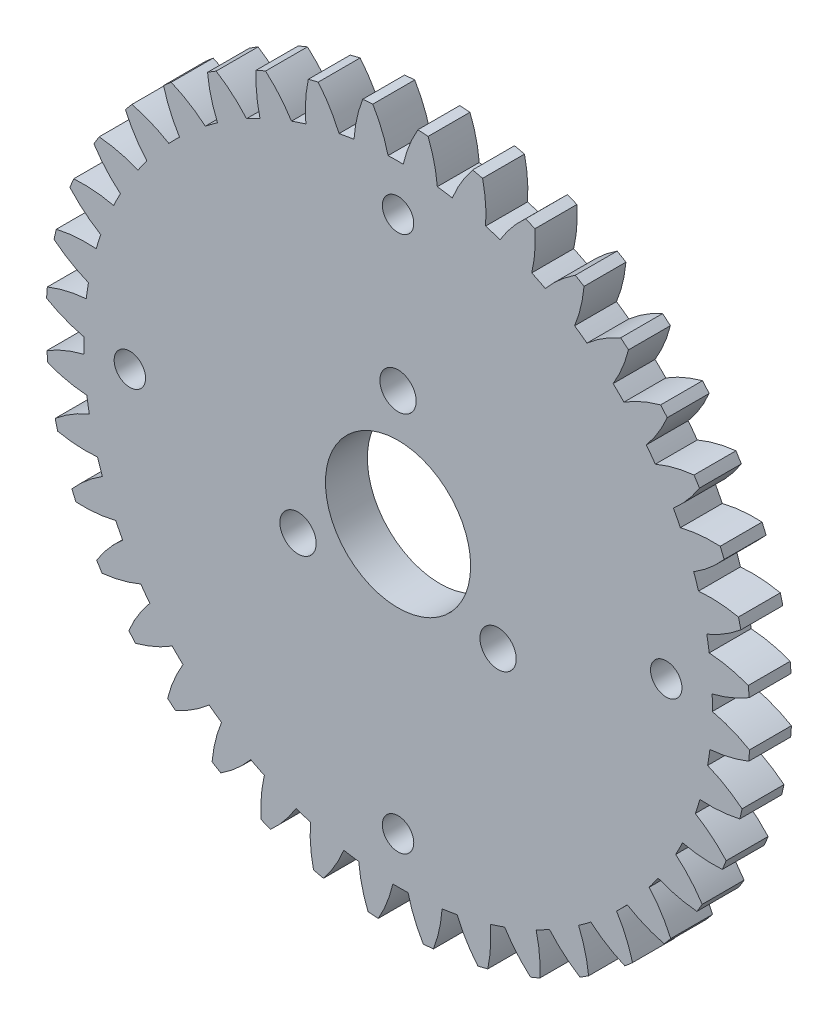
SolidWorks part; units mm, degrees
ref_plane "Front Plane" through (0, 0, 0) normal (0, 0, 1) x (1, 0, 0)
ref_plane "Top Plane" through (0, 0, 0) normal (0, 1, 0) x (1, 0, 0)
ref_plane "Right Plane" through (0, 0, 0) normal (1, 0, 0) x (0, 0, -1)
sketch "Sketch1" plane through (0, 0, 0) normal (0, 0, 1) x (1, 0, 0)
  line L0 (-15.1554, -8.75) -> (0, 0) construction
  line L1 (0, 0) -> (0, 17.5) construction
  line L2 (0, 0) -> (15.1554, -8.75) construction
  line L3 (0, 40.64) -> (0, 0) construction
  line L4 (-40.64, 0) -> (0, 0) construction
  circle A0 centre (0, 0) radius 11
  circle A1 centre (0, 0) radius 17.5 construction
  circle A2 centre (0, 17.5) radius 2.75
  circle A3 centre (15.1554, -8.75) radius 2.75
  circle A4 centre (-15.1554, -8.75) radius 2.75
  circle A5 centre (0, 40.64) radius 2.3812
  circle A7 centre (40.64, 0) radius 2.3813
  circle A8 centre (0, -40.64) radius 2.3813
  circle A9 centre (-40.64, 0) radius 2.3813
  point P12 (0, 0)
  point P22 (0, 0)
  arc B0 (-53.2553, 3.0046) -> (-47.6173, 0.7826) centre (-43.069, 20.587) ccw
  arc B1 (-47.6173, 0.7826) -> (-47.5997, -1.5139) centre (0, 0) ccw
  arc B2 (-47.5997, -1.5139) -> (-53.2029, -3.8222) centre (-42.7477, -21.2461) ccw
  arc B3 (-53.2029, -3.8222) -> (-53.0697, -5.3634) centre (0, 0) ccw
  arc B4 (-53.0697, -5.3634) -> (-47.1535, -6.676) centre (-45.7593, 13.5961) ccw
  arc B5 (-47.1535, -6.676) -> (-46.7768, -8.9415) centre (0, 0) ccw
  arc B6 (-46.7768, -8.9415) -> (-51.9499, -12.0979) centre (-38.8978, -27.6718) ccw
  arc B7 (-51.9499, -12.0979) -> (-51.5773, -13.5993) centre (0, 0) ccw
  arc B8 (-51.5773, -13.5993) -> (-45.5286, -13.9703) centre (-47.3228, 6.2704) ccw
  arc B9 (-45.5286, -13.9703) -> (-44.8022, -16.1489) centre (0, 0) ccw
  arc B10 (-44.8022, -16.1489) -> (-49.4178, -20.0758) centre (-34.0901, -33.416) ccw
  arc B11 (-49.4178, -20.0758) -> (-48.8149, -21.5003) centre (0, 0) ccw
  arc B12 (-48.8149, -21.5003) -> (-42.7826, -20.9205) centre (-47.7211, -1.2098) ccw
  arc B13 (-42.7826, -20.9205) -> (-41.7243, -22.9587) centre (0, 0) ccw
  arc B14 (-41.7243, -22.9587) -> (-45.6688, -27.5592) centre (-28.4429, -38.3375) ccw
  arc B15 (-45.6688, -27.5592) -> (-44.8505, -28.8719) centre (0, 0) ccw
  arc B16 (-44.8505, -28.8719) -> (-38.9832, -27.3556) centre (-46.9443, -8.6601) ccw
  arc B17 (-38.9832, -27.3556) -> (-37.6191, -29.2031) centre (0, 0) ccw
  arc B18 (-37.6191, -29.2031) -> (-40.7954, -34.3641) centre (-22.0955, -42.3149) ccw
  arc B19 (-40.7954, -34.3641) -> (-39.7818, -35.5326) centre (0, 0) ccw
  arc B20 (-39.7818, -35.5326) -> (-34.2239, -33.1172) centre (-45.0116, -15.8972) ccw
  arc B21 (-34.2239, -33.1172) -> (-32.5876, -34.7285) centre (0, 0) ccw
  arc B22 (-32.5876, -34.7285) -> (-34.9174, -40.3228) centre (-15.2039, -45.2505) ccw
  arc B23 (-34.9174, -40.3228) -> (-33.7334, -41.3184) centre (0, 0) ccw
  arc B24 (-33.7334, -41.3184) -> (-28.6219, -38.0632) centre (-41.9706, -22.7428) ccw
  arc B25 (-28.6219, -38.0632) -> (-26.7536, -39.3988) centre (0, 0) ccw
  arc B26 (-26.7536, -39.3988) -> (-28.1796, -45.2887) centre (-7.938, -47.0718) ccw
  arc B27 (-28.1796, -45.2887) -> (-26.8545, -46.0868) centre (0, 0) ccw
  arc B28 (-26.8545, -46.0868) -> (-22.3151, -42.072) centre (-37.8961, -29.0284) ccw
  arc B29 (-22.3151, -42.072) -> (-20.2609, -43.0989) centre (0, 0) ccw
  arc B30 (-20.2609, -43.0989) -> (-20.748, -49.1394) centre (-0.4766, -47.734) ccw
  arc B31 (-20.748, -49.1394) -> (-19.3143, -49.7203) centre (0, 0) ccw
  arc B32 (-19.3143, -49.7203) -> (-15.4588, -45.0449) centre (-32.8885, -34.5993) ccw
  arc B33 (-15.4588, -45.0449) -> (-13.2693, -45.7378) centre (0, 0) ccw
  arc B34 (-13.2693, -45.7378) -> (-12.8054, -51.7801) centre (6.9965, -47.2209) ccw
  arc B35 (-12.8054, -51.7801) -> (-11.2986, -52.1296) centre (0, 0) ccw
  arc B36 (-11.2986, -52.1296) -> (-8.2219, -46.9086) centre (-27.071, -39.3182) ccw
  arc B37 (-8.2219, -46.9086) -> (-5.951, -47.2505) centre (0, 0) ccw
  arc B38 (-5.951, -47.2505) -> (-4.5476, -53.1458) centre (14.2973, -45.545) ccw
  arc B39 (-4.5476, -53.1458) -> (-3.0046, -53.2553) centre (0, 0) ccw
  arc B40 (-3.0046, -53.2553) -> (-0.7826, -47.6173) centre (-20.587, -43.069) ccw
  arc B41 (-0.7826, -47.6173) -> (1.5139, -47.5997) centre (0, 0) ccw
  arc B42 (1.5139, -47.5997) -> (3.8222, -53.2029) centre (21.2461, -42.7477) ccw
  arc B43 (3.8222, -53.2029) -> (5.3634, -53.0697) centre (0, 0) ccw
  arc B44 (5.3634, -53.0697) -> (6.676, -47.1535) centre (-13.5961, -45.7593) ccw
  arc B45 (6.676, -47.1535) -> (8.9415, -46.7768) centre (0, 0) ccw
  arc B46 (8.9415, -46.7768) -> (12.0979, -51.9499) centre (27.6718, -38.8978) ccw
  arc B47 (12.0979, -51.9499) -> (13.5993, -51.5773) centre (0, 0) ccw
  arc B48 (13.5993, -51.5773) -> (13.9703, -45.5286) centre (-6.2704, -47.3228) ccw
  arc B49 (13.9703, -45.5286) -> (16.1489, -44.8022) centre (0, 0) ccw
  arc B50 (16.1489, -44.8022) -> (20.0758, -49.4178) centre (33.416, -34.0901) ccw
  arc B51 (20.0758, -49.4178) -> (21.5003, -48.8149) centre (0, 0) ccw
  arc B52 (21.5003, -48.8149) -> (20.9205, -42.7826) centre (1.2098, -47.7211) ccw
  arc B53 (20.9205, -42.7826) -> (22.9587, -41.7243) centre (0, 0) ccw
  arc B54 (22.9587, -41.7243) -> (27.5592, -45.6688) centre (38.3375, -28.4429) ccw
  arc B55 (27.5592, -45.6688) -> (28.8719, -44.8505) centre (0, 0) ccw
  arc B56 (28.8719, -44.8505) -> (27.3556, -38.9832) centre (8.6601, -46.9443) ccw
  arc B57 (27.3556, -38.9832) -> (29.2031, -37.6191) centre (0, 0) ccw
  arc B58 (29.2031, -37.6191) -> (34.3641, -40.7954) centre (42.3149, -22.0955) ccw
  arc B59 (34.3641, -40.7954) -> (35.5326, -39.7818) centre (0, 0) ccw
  arc B60 (35.5326, -39.7818) -> (33.1172, -34.2239) centre (15.8972, -45.0116) ccw
  arc B61 (33.1172, -34.2239) -> (34.7285, -32.5876) centre (0, 0) ccw
  arc B62 (34.7285, -32.5876) -> (40.3228, -34.9174) centre (45.2505, -15.2039) ccw
  arc B63 (40.3228, -34.9174) -> (41.3184, -33.7334) centre (0, 0) ccw
  arc B64 (41.3184, -33.7334) -> (38.0632, -28.6219) centre (22.7428, -41.9706) ccw
  arc B65 (38.0632, -28.6219) -> (39.3988, -26.7536) centre (0, 0) ccw
  arc B66 (39.3988, -26.7536) -> (45.2887, -28.1796) centre (47.0718, -7.938) ccw
  arc B67 (45.2887, -28.1796) -> (46.0868, -26.8545) centre (0, 0) ccw
  arc B68 (46.0868, -26.8545) -> (42.072, -22.3151) centre (29.0284, -37.8961) ccw
  arc B69 (42.072, -22.3151) -> (43.0989, -20.2609) centre (0, 0) ccw
  arc B70 (43.0989, -20.2609) -> (49.1394, -20.748) centre (47.734, -0.4766) ccw
  arc B71 (49.1394, -20.748) -> (49.7203, -19.3143) centre (0, 0) ccw
  arc B72 (49.7203, -19.3143) -> (45.0449, -15.4588) centre (34.5993, -32.8885) ccw
  arc B73 (45.0449, -15.4588) -> (45.7378, -13.2693) centre (0, 0) ccw
  arc B74 (45.7378, -13.2693) -> (51.7801, -12.8054) centre (47.2209, 6.9965) ccw
  arc B75 (51.7801, -12.8054) -> (52.1296, -11.2986) centre (0, 0) ccw
  arc B76 (52.1296, -11.2986) -> (46.9086, -8.2219) centre (39.3182, -27.071) ccw
  arc B77 (46.9086, -8.2219) -> (47.2505, -5.951) centre (0, 0) ccw
  arc B78 (47.2505, -5.951) -> (53.1458, -4.5476) centre (45.545, 14.2973) ccw
  arc B79 (53.1458, -4.5476) -> (53.2553, -3.0046) centre (0, 0) ccw
  arc B80 (53.2553, -3.0046) -> (47.6173, -0.7826) centre (43.069, -20.587) ccw
  arc B81 (47.6173, -0.7826) -> (47.5997, 1.5139) centre (0, 0) ccw
  arc B82 (47.5997, 1.5139) -> (53.2029, 3.8222) centre (42.7477, 21.2461) ccw
  arc B83 (53.2029, 3.8222) -> (53.0697, 5.3634) centre (0, 0) ccw
  arc B84 (53.0697, 5.3634) -> (47.1535, 6.676) centre (45.7593, -13.5961) ccw
  arc B85 (47.1535, 6.676) -> (46.7768, 8.9415) centre (0, 0) ccw
  arc B86 (46.7768, 8.9415) -> (51.9499, 12.0979) centre (38.8978, 27.6718) ccw
  arc B87 (51.9499, 12.0979) -> (51.5773, 13.5993) centre (0, 0) ccw
  arc B88 (51.5773, 13.5993) -> (45.5286, 13.9703) centre (47.3228, -6.2704) ccw
  arc B89 (45.5286, 13.9703) -> (44.8022, 16.1489) centre (0, 0) ccw
  arc B90 (44.8022, 16.1489) -> (49.4178, 20.0758) centre (34.0901, 33.416) ccw
  arc B91 (49.4178, 20.0758) -> (48.8149, 21.5003) centre (0, 0) ccw
  arc B92 (48.8149, 21.5003) -> (42.7826, 20.9205) centre (47.7211, 1.2098) ccw
  arc B93 (42.7826, 20.9205) -> (41.7243, 22.9587) centre (0, 0) ccw
  arc B94 (41.7243, 22.9587) -> (45.6688, 27.5592) centre (28.4429, 38.3375) ccw
  arc B95 (45.6688, 27.5592) -> (44.8505, 28.8719) centre (0, 0) ccw
  arc B96 (44.8505, 28.8719) -> (38.9832, 27.3556) centre (46.9443, 8.6601) ccw
  arc B97 (38.9832, 27.3556) -> (37.6191, 29.2031) centre (0, 0) ccw
  arc B98 (37.6191, 29.2031) -> (40.7954, 34.3641) centre (22.0955, 42.3149) ccw
  arc B99 (40.7954, 34.3641) -> (39.7818, 35.5326) centre (0, 0) ccw
  arc B100 (39.7818, 35.5326) -> (34.2239, 33.1172) centre (45.0116, 15.8972) ccw
  arc B101 (34.2239, 33.1172) -> (32.5876, 34.7285) centre (0, 0) ccw
  arc B102 (32.5876, 34.7285) -> (34.9174, 40.3228) centre (15.2039, 45.2505) ccw
  arc B103 (34.9174, 40.3228) -> (33.7334, 41.3184) centre (0, 0) ccw
  arc B104 (33.7334, 41.3184) -> (28.6219, 38.0632) centre (41.9706, 22.7428) ccw
  arc B105 (28.6219, 38.0632) -> (26.7536, 39.3988) centre (0, 0) ccw
  arc B106 (26.7536, 39.3988) -> (28.1796, 45.2887) centre (7.938, 47.0718) ccw
  arc B107 (28.1796, 45.2887) -> (26.8545, 46.0868) centre (0, 0) ccw
  arc B108 (26.8545, 46.0868) -> (22.3151, 42.072) centre (37.8961, 29.0284) ccw
  arc B109 (22.3151, 42.072) -> (20.2609, 43.0989) centre (0, 0) ccw
  arc B110 (20.2609, 43.0989) -> (20.748, 49.1394) centre (0.4766, 47.734) ccw
  arc B111 (20.748, 49.1394) -> (19.3143, 49.7203) centre (0, 0) ccw
  arc B112 (19.3143, 49.7203) -> (15.4588, 45.0449) centre (32.8885, 34.5993) ccw
  arc B113 (15.4588, 45.0449) -> (13.2693, 45.7378) centre (0, 0) ccw
  arc B114 (13.2693, 45.7378) -> (12.8054, 51.7801) centre (-6.9965, 47.2209) ccw
  arc B115 (12.8054, 51.7801) -> (11.2986, 52.1296) centre (0, 0) ccw
  arc B116 (11.2986, 52.1296) -> (8.2219, 46.9086) centre (27.071, 39.3182) ccw
  arc B117 (8.2219, 46.9086) -> (5.951, 47.2505) centre (0, 0) ccw
  arc B118 (5.951, 47.2505) -> (4.5476, 53.1458) centre (-14.2973, 45.545) ccw
  arc B119 (4.5476, 53.1458) -> (3.0046, 53.2553) centre (0, 0) ccw
  arc B120 (3.0046, 53.2553) -> (0.7826, 47.6173) centre (20.587, 43.069) ccw
  arc B121 (0.7826, 47.6173) -> (-1.5139, 47.5997) centre (0, 0) ccw
  arc B122 (-1.5139, 47.5997) -> (-3.8222, 53.2029) centre (-21.2461, 42.7477) ccw
  arc B123 (-3.8222, 53.2029) -> (-5.3634, 53.0697) centre (0, 0) ccw
  arc B124 (-5.3634, 53.0697) -> (-6.676, 47.1535) centre (13.5961, 45.7593) ccw
  arc B125 (-6.676, 47.1535) -> (-8.9415, 46.7768) centre (0, 0) ccw
  arc B126 (-8.9415, 46.7768) -> (-12.0979, 51.9499) centre (-27.6718, 38.8978) ccw
  arc B127 (-12.0979, 51.9499) -> (-13.5993, 51.5773) centre (0, 0) ccw
  arc B128 (-13.5993, 51.5773) -> (-13.9703, 45.5286) centre (6.2704, 47.3228) ccw
  arc B129 (-13.9703, 45.5286) -> (-16.1489, 44.8022) centre (0, 0) ccw
  arc B130 (-16.1489, 44.8022) -> (-20.0758, 49.4178) centre (-33.416, 34.0901) ccw
  arc B131 (-20.0758, 49.4178) -> (-21.5003, 48.8149) centre (0, 0) ccw
  arc B132 (-21.5003, 48.8149) -> (-20.9205, 42.7826) centre (-1.2098, 47.7211) ccw
  arc B133 (-20.9205, 42.7826) -> (-22.9587, 41.7243) centre (0, 0) ccw
  arc B134 (-22.9587, 41.7243) -> (-27.5592, 45.6688) centre (-38.3375, 28.4429) ccw
  arc B135 (-27.5592, 45.6688) -> (-28.8719, 44.8505) centre (0, 0) ccw
  arc B136 (-28.8719, 44.8505) -> (-27.3556, 38.9832) centre (-8.6601, 46.9443) ccw
  arc B137 (-27.3556, 38.9832) -> (-29.2031, 37.6191) centre (0, 0) ccw
  arc B138 (-29.2031, 37.6191) -> (-34.3641, 40.7954) centre (-42.3149, 22.0955) ccw
  arc B139 (-34.3641, 40.7954) -> (-35.5326, 39.7818) centre (0, 0) ccw
  arc B140 (-35.5326, 39.7818) -> (-33.1172, 34.2239) centre (-15.8972, 45.0116) ccw
  arc B141 (-33.1172, 34.2239) -> (-34.7285, 32.5876) centre (0, 0) ccw
  arc B142 (-34.7285, 32.5876) -> (-40.3228, 34.9174) centre (-45.2505, 15.2039) ccw
  arc B143 (-40.3228, 34.9174) -> (-41.3184, 33.7334) centre (0, 0) ccw
  arc B144 (-41.3184, 33.7334) -> (-38.0632, 28.6219) centre (-22.7428, 41.9706) ccw
  arc B145 (-38.0632, 28.6219) -> (-39.3988, 26.7536) centre (0, 0) ccw
  arc B146 (-39.3988, 26.7536) -> (-45.2887, 28.1796) centre (-47.0718, 7.938) ccw
  arc B147 (-45.2887, 28.1796) -> (-46.0868, 26.8545) centre (0, 0) ccw
  arc B148 (-46.0868, 26.8545) -> (-42.072, 22.3151) centre (-29.0284, 37.8961) ccw
  arc B149 (-42.072, 22.3151) -> (-43.0989, 20.2609) centre (0, 0) ccw
  arc B150 (-43.0989, 20.2609) -> (-49.1394, 20.748) centre (-47.734, 0.4766) ccw
  arc B151 (-49.1394, 20.748) -> (-49.7203, 19.3143) centre (0, 0) ccw
  arc B152 (-49.7203, 19.3143) -> (-45.0449, 15.4588) centre (-34.5993, 32.8885) ccw
  arc B153 (-45.0449, 15.4588) -> (-45.7378, 13.2693) centre (0, 0) ccw
  arc B154 (-45.7378, 13.2693) -> (-51.7801, 12.8054) centre (-47.2209, -6.9965) ccw
  arc B155 (-51.7801, 12.8054) -> (-52.1296, 11.2986) centre (0, 0) ccw
  arc B156 (-52.1296, 11.2986) -> (-46.9086, 8.2219) centre (-39.3182, 27.071) ccw
  arc B157 (-46.9086, 8.2219) -> (-47.2505, 5.951) centre (0, 0) ccw
  arc B158 (-47.2505, 5.951) -> (-53.1458, 4.5476) centre (-45.545, -14.2973) ccw
  arc B159 (-53.1458, 4.5476) -> (-53.2553, 3.0046) centre (0, 0) ccw
  dimension "D1" = 22
  dimension "D2" = 35
  dimension "D3" = 5.5
  dimension "D6" = 120
  dimension "D7" = 4.7625
  dimension "D5" = 120
  dimension "D8" = 40.64
  dimension "D10" = 40.64
  dimension "D4" = 3
  dimension "D9" = 4
sketch_block_instance "Center_Gear-1"
sketch_block "Center_Gear"
extrude "Boss-Extrude1" add sketch "Sketch1" along normal blind 6.35
